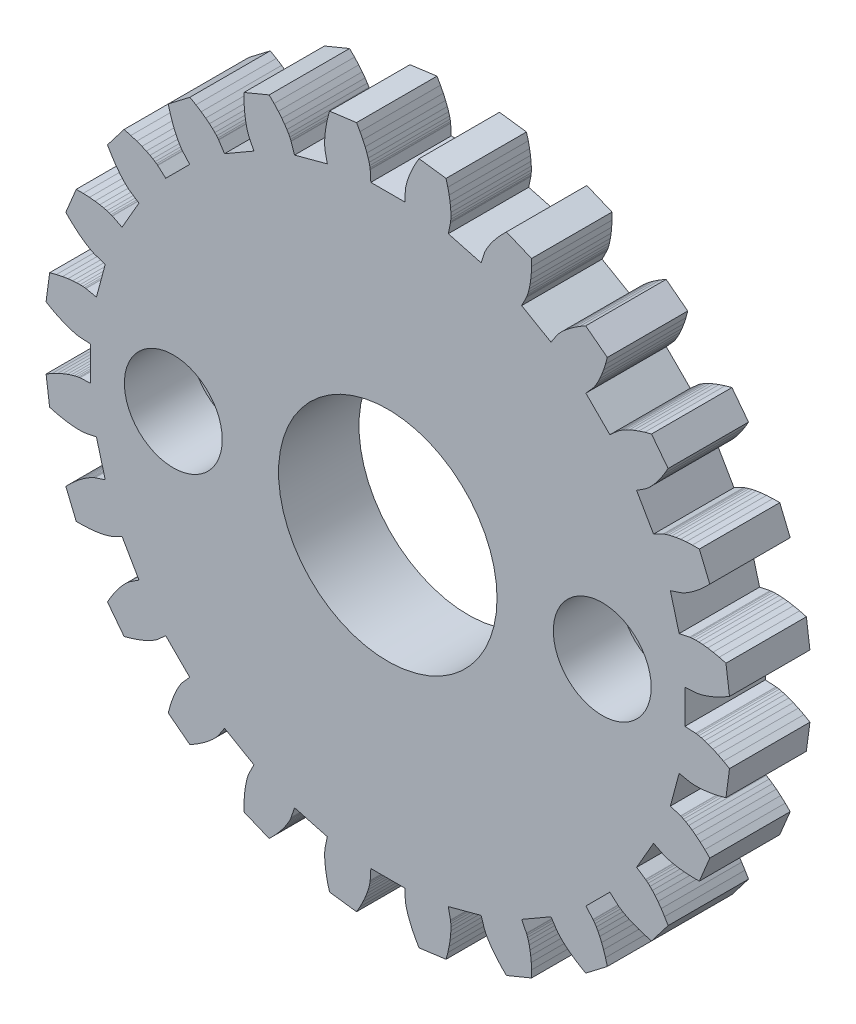
SolidWorks part; units mm, degrees
material "ABS"
ref_plane "Front Plane" through (0, 0, 0) normal (0, 0, 1) x (1, 0, 0)
ref_plane "Top Plane" through (0, 0, 0) normal (0, 1, 0) x (1, 0, 0)
ref_plane "Right Plane" through (0, 0, 0) normal (1, 0, 0) x (0, 0, -1)
sketch "Model" plane through (0, 0, 0) normal (0, 0, 1) x (1, 0, 0)
  line L0 (11.4813, -0.6559) -> (11.0819, -0.6331)
  line L1 (11.0819, -0.6331) -> (11.0819, 0.6331)
  line L2 (11.4813, 0.6559) -> (11.0819, 0.6331)
  line L3 (11.4813, 0.6559) -> (11.495, 0.6571)
  line L4 (11.495, 0.6571) -> (11.5358, 0.6626)
  line L5 (11.5358, 0.6626) -> (11.6033, 0.6749)
  line L6 (11.6033, 0.6749) -> (11.697, 0.6968)
  line L7 (11.697, 0.6968) -> (11.8158, 0.7307)
  line L8 (11.8158, 0.7307) -> (11.9589, 0.7792)
  line L9 (11.9589, 0.7792) -> (12.125, 0.8446)
  line L10 (12.125, 0.8446) -> (12.3128, 0.9294)
  line L11 (12.3128, 0.9294) -> (12.5206, 1.0358)
  line L12 (12.5206, 1.0358) -> (12.7468, 1.1658)
  line L13 (11.2598, 2.338) -> (11.2734, 2.3404)
  line L14 (11.2734, 2.3404) -> (11.3142, 2.3457)
  line L15 (11.3142, 2.3457) -> (11.3827, 2.3512)
  line L16 (11.3827, 2.3512) -> (11.4787, 2.3543)
  line L17 (11.4787, 2.3543) -> (11.6023, 2.3524)
  line L18 (11.6023, 2.3524) -> (11.7531, 2.3426)
  line L19 (11.7531, 2.3426) -> (11.9305, 2.3223)
  line L20 (11.9305, 2.3223) -> (12.1338, 2.289)
  line L21 (12.1338, 2.289) -> (12.362, 2.2401)
  line L22 (12.362, 2.2401) -> (12.6142, 2.173)
  line L23 (12.7468, 1.1658) -> (12.6142, 2.173)
  line L24 (11.2598, 2.338) -> (10.8682, 2.2567)
  line L25 (10.8682, 2.2567) -> (10.5405, 3.4797)
  line L26 (10.9203, 3.6051) -> (10.5405, 3.4797)
  line L27 (10.9203, 3.6051) -> (10.9332, 3.6098)
  line L28 (10.9332, 3.6098) -> (10.9712, 3.6257)
  line L29 (10.9712, 3.6257) -> (11.0333, 3.6551)
  line L30 (11.0333, 3.6551) -> (11.1181, 3.7004)
  line L31 (11.1181, 3.7004) -> (11.2241, 3.764)
  line L32 (11.2241, 3.764) -> (11.3497, 3.8478)
  line L33 (11.3497, 3.8478) -> (11.4933, 3.954)
  line L34 (11.4933, 3.954) -> (11.6527, 4.0845)
  line L35 (11.6527, 4.0845) -> (11.8259, 4.241)
  line L36 (11.8259, 4.241) -> (12.0107, 4.4252)
  line L37 (10.271, 5.1726) -> (10.2835, 5.1784)
  line L38 (10.2835, 5.1784) -> (10.3216, 5.1941)
  line L39 (10.3216, 5.1941) -> (10.3863, 5.2172)
  line L40 (10.3863, 5.2172) -> (10.4783, 5.245)
  line L41 (10.4783, 5.245) -> (10.5981, 5.2751)
  line L42 (10.5981, 5.2751) -> (10.7463, 5.3047)
  line L43 (10.7463, 5.3047) -> (10.9229, 5.331)
  line L44 (10.9229, 5.331) -> (11.1279, 5.3515)
  line L45 (11.1279, 5.3515) -> (11.361, 5.3633)
  line L46 (11.361, 5.3633) -> (11.622, 5.3638)
  line L47 (12.0107, 4.4252) -> (11.622, 5.3638)
  line L48 (10.271, 5.1726) -> (9.9138, 4.9927)
  line L49 (9.9138, 4.9927) -> (9.2807, 6.0892)
  line L50 (9.6151, 6.3087) -> (9.2807, 6.0892)
  line L51 (9.6151, 6.3087) -> (9.6264, 6.3166)
  line L52 (9.6264, 6.3166) -> (9.659, 6.3417)
  line L53 (9.659, 6.3417) -> (9.7113, 6.3862)
  line L54 (9.7113, 6.3862) -> (9.7815, 6.4519)
  line L55 (9.7815, 6.4519) -> (9.8675, 6.5407)
  line L56 (9.8675, 6.5407) -> (9.9671, 6.6542)
  line L57 (9.9671, 6.6542) -> (10.0783, 6.794)
  line L58 (10.0783, 6.794) -> (10.1985, 6.9613)
  line L59 (10.1985, 6.9613) -> (10.3253, 7.1573)
  line L60 (10.3253, 7.1573) -> (10.4561, 7.383)
  line L61 (8.5823, 7.6547) -> (8.5928, 7.6635)
  line L62 (8.5928, 7.6635) -> (8.6256, 7.6885)
  line L63 (8.6256, 7.6885) -> (8.6821, 7.7275)
  line L64 (8.6821, 7.7275) -> (8.7637, 7.7783)
  line L65 (8.7637, 7.7783) -> (8.8717, 7.8384)
  line L66 (8.8717, 7.8384) -> (9.0072, 7.9053)
  line L67 (9.0072, 7.9053) -> (9.1709, 7.9764)
  line L68 (9.1709, 7.9764) -> (9.3636, 8.0492)
  line L69 (9.3636, 8.0492) -> (9.5858, 8.121)
  line L70 (9.5858, 8.121) -> (9.8377, 8.189)
  line L71 (10.4561, 7.383) -> (9.8377, 8.189)
  line L72 (8.5823, 7.6547) -> (8.2838, 7.3885)
  line L73 (8.2838, 7.3885) -> (7.3885, 8.2838)
  line L74 (7.6547, 8.5823) -> (7.3885, 8.2838)
  line L75 (7.6547, 8.5823) -> (7.6635, 8.5928)
  line L76 (7.6635, 8.5928) -> (7.6885, 8.6256)
  line L77 (7.6885, 8.6256) -> (7.7275, 8.6821)
  line L78 (7.7275, 8.6821) -> (7.7783, 8.7637)
  line L79 (7.7783, 8.7637) -> (7.8384, 8.8717)
  line L80 (7.8384, 8.8717) -> (7.9053, 9.0072)
  line L81 (7.9053, 9.0072) -> (7.9764, 9.1709)
  line L82 (7.9764, 9.1709) -> (8.0492, 9.3636)
  line L83 (8.0492, 9.3636) -> (8.121, 9.5858)
  line L84 (8.121, 9.5858) -> (8.189, 9.8377)
  line L85 (6.3087, 9.6151) -> (6.3166, 9.6264)
  line L86 (6.3166, 9.6264) -> (6.3417, 9.659)
  line L87 (6.3417, 9.659) -> (6.3862, 9.7113)
  line L88 (6.3862, 9.7113) -> (6.4519, 9.7815)
  line L89 (6.4519, 9.7815) -> (6.5407, 9.8675)
  line L90 (6.5407, 9.8675) -> (6.6542, 9.9671)
  line L91 (6.6542, 9.9671) -> (6.794, 10.0783)
  line L92 (6.794, 10.0783) -> (6.9613, 10.1985)
  line L93 (6.9613, 10.1985) -> (7.1573, 10.3253)
  line L94 (7.1573, 10.3253) -> (7.383, 10.4561)
  line L95 (8.189, 9.8377) -> (7.383, 10.4561)
  line L96 (6.3087, 9.6151) -> (6.0892, 9.2807)
  line L97 (6.0892, 9.2807) -> (4.9927, 9.9138)
  line L98 (5.1726, 10.271) -> (4.9927, 9.9138)
  line L99 (5.1726, 10.271) -> (5.1784, 10.2835)
  line L100 (5.1784, 10.2835) -> (5.1941, 10.3216)
  line L101 (5.1941, 10.3216) -> (5.2172, 10.3863)
  line L102 (5.2172, 10.3863) -> (5.245, 10.4783)
  line L103 (5.245, 10.4783) -> (5.2751, 10.5981)
  line L104 (5.2751, 10.5981) -> (5.3047, 10.7463)
  line L105 (5.3047, 10.7463) -> (5.331, 10.9229)
  line L106 (5.331, 10.9229) -> (5.3515, 11.1279)
  line L107 (5.3515, 11.1279) -> (5.3633, 11.361)
  line L108 (5.3633, 11.361) -> (5.3638, 11.622)
  line L109 (3.6051, 10.9203) -> (3.6098, 10.9332)
  line L110 (3.6098, 10.9332) -> (3.6257, 10.9712)
  line L111 (3.6257, 10.9712) -> (3.6551, 11.0333)
  line L112 (3.6551, 11.0333) -> (3.7004, 11.1181)
  line L113 (3.7004, 11.1181) -> (3.764, 11.2241)
  line L114 (3.764, 11.2241) -> (3.8478, 11.3497)
  line L115 (3.8478, 11.3497) -> (3.954, 11.4933)
  line L116 (3.954, 11.4933) -> (4.0845, 11.6527)
  line L117 (4.0845, 11.6527) -> (4.241, 11.8259)
  line L118 (4.241, 11.8259) -> (4.4252, 12.0107)
  line L119 (5.3638, 11.622) -> (4.4252, 12.0107)
  line L120 (3.6051, 10.9203) -> (3.4797, 10.5405)
  line L121 (3.4797, 10.5405) -> (2.2567, 10.8682)
  line L122 (2.338, 11.2598) -> (2.2567, 10.8682)
  line L123 (2.338, 11.2598) -> (2.3404, 11.2734)
  line L124 (2.3404, 11.2734) -> (2.3457, 11.3142)
  line L125 (2.3457, 11.3142) -> (2.3512, 11.3827)
  line L126 (2.3512, 11.3827) -> (2.3543, 11.4787)
  line L127 (2.3543, 11.4787) -> (2.3524, 11.6023)
  line L128 (2.3524, 11.6023) -> (2.3426, 11.7531)
  line L129 (2.3426, 11.7531) -> (2.3223, 11.9305)
  line L130 (2.3223, 11.9305) -> (2.289, 12.1338)
  line L131 (2.289, 12.1338) -> (2.2401, 12.362)
  line L132 (2.2401, 12.362) -> (2.173, 12.6142)
  line L133 (0.6559, 11.4813) -> (0.6571, 11.495)
  line L134 (0.6571, 11.495) -> (0.6626, 11.5358)
  line L135 (0.6626, 11.5358) -> (0.6749, 11.6033)
  line L136 (0.6749, 11.6033) -> (0.6968, 11.697)
  line L137 (0.6968, 11.697) -> (0.7307, 11.8158)
  line L138 (0.7307, 11.8158) -> (0.7792, 11.9589)
  line L139 (0.7792, 11.9589) -> (0.8446, 12.125)
  line L140 (0.8446, 12.125) -> (0.9294, 12.3128)
  line L141 (0.9294, 12.3128) -> (1.0358, 12.5206)
  line L142 (1.0358, 12.5206) -> (1.1658, 12.7468)
  line L143 (2.173, 12.6142) -> (1.1658, 12.7468)
  line L144 (0.6559, 11.4813) -> (0.6331, 11.0819)
  line L145 (0.6331, 11.0819) -> (-0.6331, 11.0819)
  line L146 (-0.6559, 11.4813) -> (-0.6331, 11.0819)
  line L147 (-0.6559, 11.4813) -> (-0.6571, 11.495)
  line L148 (-0.6571, 11.495) -> (-0.6626, 11.5358)
  line L149 (-0.6626, 11.5358) -> (-0.6749, 11.6033)
  line L150 (-0.6749, 11.6033) -> (-0.6968, 11.697)
  line L151 (-0.6968, 11.697) -> (-0.7307, 11.8158)
  line L152 (-0.7307, 11.8158) -> (-0.7792, 11.9589)
  line L153 (-0.7792, 11.9589) -> (-0.8446, 12.125)
  line L154 (-0.8446, 12.125) -> (-0.9294, 12.3128)
  line L155 (-0.9294, 12.3128) -> (-1.0358, 12.5206)
  line L156 (-1.0358, 12.5206) -> (-1.1658, 12.7468)
  line L157 (-2.338, 11.2598) -> (-2.3404, 11.2734)
  line L158 (-2.3404, 11.2734) -> (-2.3457, 11.3142)
  line L159 (-2.3457, 11.3142) -> (-2.3512, 11.3827)
  line L160 (-2.3512, 11.3827) -> (-2.3543, 11.4787)
  line L161 (-2.3543, 11.4787) -> (-2.3524, 11.6023)
  line L162 (-2.3524, 11.6023) -> (-2.3426, 11.7531)
  line L163 (-2.3426, 11.7531) -> (-2.3223, 11.9305)
  line L164 (-2.3223, 11.9305) -> (-2.289, 12.1338)
  line L165 (-2.289, 12.1338) -> (-2.2401, 12.362)
  line L166 (-2.2401, 12.362) -> (-2.173, 12.6142)
  line L167 (-1.1658, 12.7468) -> (-2.173, 12.6142)
  line L168 (-2.338, 11.2598) -> (-2.2567, 10.8682)
  line L169 (-2.2567, 10.8682) -> (-3.4797, 10.5405)
  line L170 (-3.6051, 10.9203) -> (-3.4797, 10.5405)
  line L171 (-3.6051, 10.9203) -> (-3.6098, 10.9332)
  line L172 (-3.6098, 10.9332) -> (-3.6257, 10.9712)
  line L173 (-3.6257, 10.9712) -> (-3.6551, 11.0333)
  line L174 (-3.6551, 11.0333) -> (-3.7004, 11.1181)
  line L175 (-3.7004, 11.1181) -> (-3.764, 11.2241)
  line L176 (-3.764, 11.2241) -> (-3.8478, 11.3497)
  line L177 (-3.8478, 11.3497) -> (-3.954, 11.4933)
  line L178 (-3.954, 11.4933) -> (-4.0845, 11.6527)
  line L179 (-4.0845, 11.6527) -> (-4.241, 11.8259)
  line L180 (-4.241, 11.8259) -> (-4.4252, 12.0107)
  line L181 (-5.1726, 10.271) -> (-5.1784, 10.2835)
  line L182 (-5.1784, 10.2835) -> (-5.1941, 10.3216)
  line L183 (-5.1941, 10.3216) -> (-5.2172, 10.3863)
  line L184 (-5.2172, 10.3863) -> (-5.245, 10.4783)
  line L185 (-5.245, 10.4783) -> (-5.2751, 10.5981)
  line L186 (-5.2751, 10.5981) -> (-5.3047, 10.7463)
  line L187 (-5.3047, 10.7463) -> (-5.331, 10.9229)
  line L188 (-5.331, 10.9229) -> (-5.3515, 11.1279)
  line L189 (-5.3515, 11.1279) -> (-5.3633, 11.361)
  line L190 (-5.3633, 11.361) -> (-5.3638, 11.622)
  line L191 (-4.4252, 12.0107) -> (-5.3638, 11.622)
  line L192 (-5.1726, 10.271) -> (-4.9927, 9.9138)
  line L193 (-4.9927, 9.9138) -> (-6.0892, 9.2807)
  line L194 (-6.3087, 9.6151) -> (-6.0892, 9.2807)
  line L195 (-6.3087, 9.6151) -> (-6.3166, 9.6264)
  line L196 (-6.3166, 9.6264) -> (-6.3417, 9.659)
  line L197 (-6.3417, 9.659) -> (-6.3862, 9.7113)
  line L198 (-6.3862, 9.7113) -> (-6.4519, 9.7815)
  line L199 (-6.4519, 9.7815) -> (-6.5407, 9.8675)
  line L200 (-6.5407, 9.8675) -> (-6.6542, 9.9671)
  line L201 (-6.6542, 9.9671) -> (-6.794, 10.0783)
  line L202 (-6.794, 10.0783) -> (-6.9613, 10.1985)
  line L203 (-6.9613, 10.1985) -> (-7.1573, 10.3253)
  line L204 (-7.1573, 10.3253) -> (-7.383, 10.4561)
  line L205 (-7.6547, 8.5823) -> (-7.6635, 8.5928)
  line L206 (-7.6635, 8.5928) -> (-7.6885, 8.6256)
  line L207 (-7.6885, 8.6256) -> (-7.7275, 8.6821)
  line L208 (-7.7275, 8.6821) -> (-7.7783, 8.7637)
  line L209 (-7.7783, 8.7637) -> (-7.8384, 8.8717)
  line L210 (-7.8384, 8.8717) -> (-7.9053, 9.0072)
  line L211 (-7.9053, 9.0072) -> (-7.9764, 9.1709)
  line L212 (-7.9764, 9.1709) -> (-8.0492, 9.3636)
  line L213 (-8.0492, 9.3636) -> (-8.121, 9.5858)
  line L214 (-8.121, 9.5858) -> (-8.189, 9.8377)
  line L215 (-7.383, 10.4561) -> (-8.189, 9.8377)
  line L216 (-7.6547, 8.5823) -> (-7.3885, 8.2838)
  line L217 (-7.3885, 8.2838) -> (-8.2838, 7.3885)
  line L218 (-8.5823, 7.6547) -> (-8.2838, 7.3885)
  line L219 (-8.5823, 7.6547) -> (-8.5928, 7.6635)
  line L220 (-8.5928, 7.6635) -> (-8.6256, 7.6885)
  line L221 (-8.6256, 7.6885) -> (-8.6821, 7.7275)
  line L222 (-8.6821, 7.7275) -> (-8.7637, 7.7783)
  line L223 (-8.7637, 7.7783) -> (-8.8717, 7.8384)
  line L224 (-8.8717, 7.8384) -> (-9.0072, 7.9053)
  line L225 (-9.0072, 7.9053) -> (-9.1709, 7.9764)
  line L226 (-9.1709, 7.9764) -> (-9.3636, 8.0492)
  line L227 (-9.3636, 8.0492) -> (-9.5858, 8.121)
  line L228 (-9.5858, 8.121) -> (-9.8377, 8.189)
  line L229 (-9.6151, 6.3087) -> (-9.6264, 6.3166)
  line L230 (-9.6264, 6.3166) -> (-9.659, 6.3417)
  line L231 (-9.659, 6.3417) -> (-9.7113, 6.3862)
  line L232 (-9.7113, 6.3862) -> (-9.7815, 6.4519)
  line L233 (-9.7815, 6.4519) -> (-9.8675, 6.5407)
  line L234 (-9.8675, 6.5407) -> (-9.9671, 6.6542)
  line L235 (-9.9671, 6.6542) -> (-10.0783, 6.794)
  line L236 (-10.0783, 6.794) -> (-10.1985, 6.9613)
  line L237 (-10.1985, 6.9613) -> (-10.3253, 7.1573)
  line L238 (-10.3253, 7.1573) -> (-10.4561, 7.383)
  line L239 (-9.8377, 8.189) -> (-10.4561, 7.383)
  line L240 (-9.6151, 6.3087) -> (-9.2807, 6.0892)
  line L241 (-9.2807, 6.0892) -> (-9.9138, 4.9927)
  line L242 (-10.271, 5.1726) -> (-9.9138, 4.9927)
  line L243 (-10.271, 5.1726) -> (-10.2835, 5.1784)
  line L244 (-10.2835, 5.1784) -> (-10.3216, 5.1941)
  line L245 (-10.3216, 5.1941) -> (-10.3863, 5.2172)
  line L246 (-10.3863, 5.2172) -> (-10.4783, 5.245)
  line L247 (-10.4783, 5.245) -> (-10.5981, 5.2751)
  line L248 (-10.5981, 5.2751) -> (-10.7463, 5.3047)
  line L249 (-10.7463, 5.3047) -> (-10.9229, 5.331)
  line L250 (-10.9229, 5.331) -> (-11.1279, 5.3515)
  line L251 (-11.1279, 5.3515) -> (-11.361, 5.3633)
  line L252 (-11.361, 5.3633) -> (-11.622, 5.3638)
  line L253 (-10.9203, 3.6051) -> (-10.9332, 3.6098)
  line L254 (-10.9332, 3.6098) -> (-10.9712, 3.6257)
  line L255 (-10.9712, 3.6257) -> (-11.0333, 3.6551)
  line L256 (-11.0333, 3.6551) -> (-11.1181, 3.7004)
  line L257 (-11.1181, 3.7004) -> (-11.2241, 3.764)
  line L258 (-11.2241, 3.764) -> (-11.3497, 3.8478)
  line L259 (-11.3497, 3.8478) -> (-11.4933, 3.954)
  line L260 (-11.4933, 3.954) -> (-11.6527, 4.0845)
  line L261 (-11.6527, 4.0845) -> (-11.8259, 4.241)
  line L262 (-11.8259, 4.241) -> (-12.0107, 4.4252)
  line L263 (-11.622, 5.3638) -> (-12.0107, 4.4252)
  line L264 (-10.9203, 3.6051) -> (-10.5405, 3.4797)
  line L265 (-10.5405, 3.4797) -> (-10.8682, 2.2567)
  line L266 (-11.2598, 2.338) -> (-10.8682, 2.2567)
  line L267 (-11.2598, 2.338) -> (-11.2734, 2.3404)
  line L268 (-11.2734, 2.3404) -> (-11.3142, 2.3457)
  line L269 (-11.3142, 2.3457) -> (-11.3827, 2.3512)
  line L270 (-11.3827, 2.3512) -> (-11.4787, 2.3543)
  line L271 (-11.4787, 2.3543) -> (-11.6023, 2.3524)
  line L272 (-11.6023, 2.3524) -> (-11.7531, 2.3426)
  line L273 (-11.7531, 2.3426) -> (-11.9305, 2.3223)
  line L274 (-11.9305, 2.3223) -> (-12.1338, 2.289)
  line L275 (-12.1338, 2.289) -> (-12.362, 2.2401)
  line L276 (-12.362, 2.2401) -> (-12.6142, 2.173)
  line L277 (-11.4813, 0.6559) -> (-11.495, 0.6571)
  line L278 (-11.495, 0.6571) -> (-11.5358, 0.6626)
  line L279 (-11.5358, 0.6626) -> (-11.6033, 0.6749)
  line L280 (-11.6033, 0.6749) -> (-11.697, 0.6968)
  line L281 (-11.697, 0.6968) -> (-11.8158, 0.7307)
  line L282 (-11.8158, 0.7307) -> (-11.9589, 0.7792)
  line L283 (-11.9589, 0.7792) -> (-12.125, 0.8446)
  line L284 (-12.125, 0.8446) -> (-12.3128, 0.9294)
  line L285 (-12.3128, 0.9294) -> (-12.5206, 1.0358)
  line L286 (-12.5206, 1.0358) -> (-12.7468, 1.1658)
  line L287 (-12.6142, 2.173) -> (-12.7468, 1.1658)
  line L288 (-11.4813, 0.6559) -> (-11.0819, 0.6331)
  line L289 (-11.0819, 0.6331) -> (-11.0819, -0.6331)
  line L290 (-11.4813, -0.6559) -> (-11.0819, -0.6331)
  line L291 (-11.4813, -0.6559) -> (-11.495, -0.6571)
  line L292 (-11.495, -0.6571) -> (-11.5358, -0.6626)
  line L293 (-11.5358, -0.6626) -> (-11.6033, -0.6749)
  line L294 (-11.6033, -0.6749) -> (-11.697, -0.6968)
  line L295 (-11.697, -0.6968) -> (-11.8158, -0.7307)
  line L296 (-11.8158, -0.7307) -> (-11.9589, -0.7792)
  line L297 (-11.9589, -0.7792) -> (-12.125, -0.8446)
  line L298 (-12.125, -0.8446) -> (-12.3128, -0.9294)
  line L299 (-12.3128, -0.9294) -> (-12.5206, -1.0358)
  line L300 (-12.5206, -1.0358) -> (-12.7468, -1.1658)
  line L301 (-11.2598, -2.338) -> (-11.2734, -2.3404)
  line L302 (-11.2734, -2.3404) -> (-11.3142, -2.3457)
  line L303 (-11.3142, -2.3457) -> (-11.3827, -2.3512)
  line L304 (-11.3827, -2.3512) -> (-11.4787, -2.3543)
  line L305 (-11.4787, -2.3543) -> (-11.6023, -2.3524)
  line L306 (-11.6023, -2.3524) -> (-11.7531, -2.3426)
  line L307 (-11.7531, -2.3426) -> (-11.9305, -2.3223)
  line L308 (-11.9305, -2.3223) -> (-12.1338, -2.289)
  line L309 (-12.1338, -2.289) -> (-12.362, -2.2401)
  line L310 (-12.362, -2.2401) -> (-12.6142, -2.173)
  line L311 (-12.7468, -1.1658) -> (-12.6142, -2.173)
  line L312 (-11.2598, -2.338) -> (-10.8682, -2.2567)
  line L313 (-10.8682, -2.2567) -> (-10.5405, -3.4797)
  line L314 (-10.9203, -3.6051) -> (-10.5405, -3.4797)
  line L315 (-10.9203, -3.6051) -> (-10.9332, -3.6098)
  line L316 (-10.9332, -3.6098) -> (-10.9712, -3.6257)
  line L317 (-10.9712, -3.6257) -> (-11.0333, -3.6551)
  line L318 (-11.0333, -3.6551) -> (-11.1181, -3.7004)
  line L319 (-11.1181, -3.7004) -> (-11.2241, -3.764)
  line L320 (-11.2241, -3.764) -> (-11.3497, -3.8478)
  line L321 (-11.3497, -3.8478) -> (-11.4933, -3.954)
  line L322 (-11.4933, -3.954) -> (-11.6527, -4.0845)
  line L323 (-11.6527, -4.0845) -> (-11.8259, -4.241)
  line L324 (-11.8259, -4.241) -> (-12.0107, -4.4252)
  line L325 (-10.271, -5.1726) -> (-10.2835, -5.1784)
  line L326 (-10.2835, -5.1784) -> (-10.3216, -5.1941)
  line L327 (-10.3216, -5.1941) -> (-10.3863, -5.2172)
  line L328 (-10.3863, -5.2172) -> (-10.4783, -5.245)
  line L329 (-10.4783, -5.245) -> (-10.5981, -5.2751)
  line L330 (-10.5981, -5.2751) -> (-10.7463, -5.3047)
  line L331 (-10.7463, -5.3047) -> (-10.9229, -5.331)
  line L332 (-10.9229, -5.331) -> (-11.1279, -5.3515)
  line L333 (-11.1279, -5.3515) -> (-11.361, -5.3633)
  line L334 (-11.361, -5.3633) -> (-11.622, -5.3638)
  line L335 (-12.0107, -4.4252) -> (-11.622, -5.3638)
  line L336 (-10.271, -5.1726) -> (-9.9138, -4.9927)
  line L337 (-9.9138, -4.9927) -> (-9.2807, -6.0892)
  line L338 (-9.6151, -6.3087) -> (-9.2807, -6.0892)
  line L339 (-9.6151, -6.3087) -> (-9.6264, -6.3166)
  line L340 (-9.6264, -6.3166) -> (-9.659, -6.3417)
  line L341 (-9.659, -6.3417) -> (-9.7113, -6.3862)
  line L342 (-9.7113, -6.3862) -> (-9.7815, -6.4519)
  line L343 (-9.7815, -6.4519) -> (-9.8675, -6.5407)
  line L344 (-9.8675, -6.5407) -> (-9.9671, -6.6542)
  line L345 (-9.9671, -6.6542) -> (-10.0783, -6.794)
  line L346 (-10.0783, -6.794) -> (-10.1985, -6.9613)
  line L347 (-10.1985, -6.9613) -> (-10.3253, -7.1573)
  line L348 (-10.3253, -7.1573) -> (-10.4561, -7.383)
  line L349 (-8.5823, -7.6547) -> (-8.5928, -7.6635)
  line L350 (-8.5928, -7.6635) -> (-8.6256, -7.6885)
  line L351 (-8.6256, -7.6885) -> (-8.6821, -7.7275)
  line L352 (-8.6821, -7.7275) -> (-8.7637, -7.7783)
  line L353 (-8.7637, -7.7783) -> (-8.8717, -7.8384)
  line L354 (-8.8717, -7.8384) -> (-9.0072, -7.9053)
  line L355 (-9.0072, -7.9053) -> (-9.1709, -7.9764)
  line L356 (-9.1709, -7.9764) -> (-9.3636, -8.0492)
  line L357 (-9.3636, -8.0492) -> (-9.5858, -8.121)
  line L358 (-9.5858, -8.121) -> (-9.8377, -8.189)
  line L359 (-10.4561, -7.383) -> (-9.8377, -8.189)
  line L360 (-8.5823, -7.6547) -> (-8.2838, -7.3885)
  line L361 (-8.2838, -7.3885) -> (-7.3885, -8.2838)
  line L362 (-7.6547, -8.5823) -> (-7.3885, -8.2838)
  line L363 (-7.6547, -8.5823) -> (-7.6635, -8.5928)
  line L364 (-7.6635, -8.5928) -> (-7.6885, -8.6256)
  line L365 (-7.6885, -8.6256) -> (-7.7275, -8.6821)
  line L366 (-7.7275, -8.6821) -> (-7.7783, -8.7637)
  line L367 (-7.7783, -8.7637) -> (-7.8384, -8.8717)
  line L368 (-7.8384, -8.8717) -> (-7.9053, -9.0072)
  line L369 (-7.9053, -9.0072) -> (-7.9764, -9.1709)
  line L370 (-7.9764, -9.1709) -> (-8.0492, -9.3636)
  line L371 (-8.0492, -9.3636) -> (-8.121, -9.5858)
  line L372 (-8.121, -9.5858) -> (-8.189, -9.8377)
  line L373 (-6.3087, -9.6151) -> (-6.3166, -9.6264)
  line L374 (-6.3166, -9.6264) -> (-6.3417, -9.659)
  line L375 (-6.3417, -9.659) -> (-6.3862, -9.7113)
  line L376 (-6.3862, -9.7113) -> (-6.4519, -9.7815)
  line L377 (-6.4519, -9.7815) -> (-6.5407, -9.8675)
  line L378 (-6.5407, -9.8675) -> (-6.6542, -9.9671)
  line L379 (-6.6542, -9.9671) -> (-6.794, -10.0783)
  line L380 (-6.794, -10.0783) -> (-6.9613, -10.1985)
  line L381 (-6.9613, -10.1985) -> (-7.1573, -10.3253)
  line L382 (-7.1573, -10.3253) -> (-7.383, -10.4561)
  line L383 (-8.189, -9.8377) -> (-7.383, -10.4561)
  line L384 (-6.3087, -9.6151) -> (-6.0892, -9.2807)
  line L385 (-6.0892, -9.2807) -> (-4.9927, -9.9138)
  line L386 (-5.1726, -10.271) -> (-4.9927, -9.9138)
  line L387 (-5.1726, -10.271) -> (-5.1784, -10.2835)
  line L388 (-5.1784, -10.2835) -> (-5.1941, -10.3216)
  line L389 (-5.1941, -10.3216) -> (-5.2172, -10.3863)
  line L390 (-5.2172, -10.3863) -> (-5.245, -10.4783)
  line L391 (-5.245, -10.4783) -> (-5.2751, -10.5981)
  line L392 (-5.2751, -10.5981) -> (-5.3047, -10.7463)
  line L393 (-5.3047, -10.7463) -> (-5.331, -10.9229)
  line L394 (-5.331, -10.9229) -> (-5.3515, -11.1279)
  line L395 (-5.3515, -11.1279) -> (-5.3633, -11.361)
  line L396 (-5.3633, -11.361) -> (-5.3638, -11.622)
  line L397 (-3.6051, -10.9203) -> (-3.6098, -10.9332)
  line L398 (-3.6098, -10.9332) -> (-3.6257, -10.9712)
  line L399 (-3.6257, -10.9712) -> (-3.6551, -11.0333)
  line L400 (-3.6551, -11.0333) -> (-3.7004, -11.1181)
  line L401 (-3.7004, -11.1181) -> (-3.764, -11.2241)
  line L402 (-3.764, -11.2241) -> (-3.8478, -11.3497)
  line L403 (-3.8478, -11.3497) -> (-3.954, -11.4933)
  line L404 (-3.954, -11.4933) -> (-4.0845, -11.6527)
  line L405 (-4.0845, -11.6527) -> (-4.241, -11.8259)
  line L406 (-4.241, -11.8259) -> (-4.4252, -12.0107)
  line L407 (-5.3638, -11.622) -> (-4.4252, -12.0107)
  line L408 (-3.6051, -10.9203) -> (-3.4797, -10.5405)
  line L409 (-3.4797, -10.5405) -> (-2.2567, -10.8682)
  line L410 (-2.338, -11.2598) -> (-2.2567, -10.8682)
  line L411 (-2.338, -11.2598) -> (-2.3404, -11.2734)
  line L412 (-2.3404, -11.2734) -> (-2.3457, -11.3142)
  line L413 (-2.3457, -11.3142) -> (-2.3512, -11.3827)
  line L414 (-2.3512, -11.3827) -> (-2.3543, -11.4787)
  line L415 (-2.3543, -11.4787) -> (-2.3524, -11.6023)
  line L416 (-2.3524, -11.6023) -> (-2.3426, -11.7531)
  line L417 (-2.3426, -11.7531) -> (-2.3223, -11.9305)
  line L418 (-2.3223, -11.9305) -> (-2.289, -12.1338)
  line L419 (-2.289, -12.1338) -> (-2.2401, -12.362)
  line L420 (-2.2401, -12.362) -> (-2.173, -12.6142)
  line L421 (-0.6559, -11.4813) -> (-0.6571, -11.495)
  line L422 (-0.6571, -11.495) -> (-0.6626, -11.5358)
  line L423 (-0.6626, -11.5358) -> (-0.6749, -11.6033)
  line L424 (-0.6749, -11.6033) -> (-0.6968, -11.697)
  line L425 (-0.6968, -11.697) -> (-0.7307, -11.8158)
  line L426 (-0.7307, -11.8158) -> (-0.7792, -11.9589)
  line L427 (-0.7792, -11.9589) -> (-0.8446, -12.125)
  line L428 (-0.8446, -12.125) -> (-0.9294, -12.3128)
  line L429 (-0.9294, -12.3128) -> (-1.0358, -12.5206)
  line L430 (-1.0358, -12.5206) -> (-1.1658, -12.7468)
  line L431 (-2.173, -12.6142) -> (-1.1658, -12.7468)
  line L432 (-0.6559, -11.4813) -> (-0.6331, -11.0819)
  line L433 (-0.6331, -11.0819) -> (0.6331, -11.0819)
  line L434 (0.6559, -11.4813) -> (0.6331, -11.0819)
  line L435 (0.6559, -11.4813) -> (0.6571, -11.495)
  line L436 (0.6571, -11.495) -> (0.6626, -11.5358)
  line L437 (0.6626, -11.5358) -> (0.6749, -11.6033)
  line L438 (0.6749, -11.6033) -> (0.6968, -11.697)
  line L439 (0.6968, -11.697) -> (0.7307, -11.8158)
  line L440 (0.7307, -11.8158) -> (0.7792, -11.9589)
  line L441 (0.7792, -11.9589) -> (0.8446, -12.125)
  line L442 (0.8446, -12.125) -> (0.9294, -12.3128)
  line L443 (0.9294, -12.3128) -> (1.0358, -12.5206)
  line L444 (1.0358, -12.5206) -> (1.1658, -12.7468)
  line L445 (2.338, -11.2598) -> (2.3404, -11.2734)
  line L446 (2.3404, -11.2734) -> (2.3457, -11.3142)
  line L447 (2.3457, -11.3142) -> (2.3512, -11.3827)
  line L448 (2.3512, -11.3827) -> (2.3543, -11.4787)
  line L449 (2.3543, -11.4787) -> (2.3524, -11.6023)
  line L450 (2.3524, -11.6023) -> (2.3426, -11.7531)
  line L451 (2.3426, -11.7531) -> (2.3223, -11.9305)
  line L452 (2.3223, -11.9305) -> (2.289, -12.1338)
  line L453 (2.289, -12.1338) -> (2.2401, -12.362)
  line L454 (2.2401, -12.362) -> (2.173, -12.6142)
  line L455 (1.1658, -12.7468) -> (2.173, -12.6142)
  line L456 (2.338, -11.2598) -> (2.2567, -10.8682)
  line L457 (2.2567, -10.8682) -> (3.4797, -10.5405)
  line L458 (3.6051, -10.9203) -> (3.4797, -10.5405)
  line L459 (3.6051, -10.9203) -> (3.6098, -10.9332)
  line L460 (3.6098, -10.9332) -> (3.6257, -10.9712)
  line L461 (3.6257, -10.9712) -> (3.6551, -11.0333)
  line L462 (3.6551, -11.0333) -> (3.7004, -11.1181)
  line L463 (3.7004, -11.1181) -> (3.764, -11.2241)
  line L464 (3.764, -11.2241) -> (3.8478, -11.3497)
  line L465 (3.8478, -11.3497) -> (3.954, -11.4933)
  line L466 (3.954, -11.4933) -> (4.0845, -11.6527)
  line L467 (4.0845, -11.6527) -> (4.241, -11.8259)
  line L468 (4.241, -11.8259) -> (4.4252, -12.0107)
  line L469 (5.1726, -10.271) -> (5.1784, -10.2835)
  line L470 (5.1784, -10.2835) -> (5.1941, -10.3216)
  line L471 (5.1941, -10.3216) -> (5.2172, -10.3863)
  line L472 (5.2172, -10.3863) -> (5.245, -10.4783)
  line L473 (5.245, -10.4783) -> (5.2751, -10.5981)
  line L474 (5.2751, -10.5981) -> (5.3047, -10.7463)
  line L475 (5.3047, -10.7463) -> (5.331, -10.9229)
  line L476 (5.331, -10.9229) -> (5.3515, -11.1279)
  line L477 (5.3515, -11.1279) -> (5.3633, -11.361)
  line L478 (5.3633, -11.361) -> (5.3638, -11.622)
  line L479 (4.4252, -12.0107) -> (5.3638, -11.622)
  line L480 (5.1726, -10.271) -> (4.9927, -9.9138)
  line L481 (4.9927, -9.9138) -> (6.0892, -9.2807)
  line L482 (6.3087, -9.6151) -> (6.0892, -9.2807)
  line L483 (6.3087, -9.6151) -> (6.3166, -9.6264)
  line L484 (6.3166, -9.6264) -> (6.3417, -9.659)
  line L485 (6.3417, -9.659) -> (6.3862, -9.7113)
  line L486 (6.3862, -9.7113) -> (6.4519, -9.7815)
  line L487 (6.4519, -9.7815) -> (6.5407, -9.8675)
  line L488 (6.5407, -9.8675) -> (6.6542, -9.9671)
  line L489 (6.6542, -9.9671) -> (6.794, -10.0783)
  line L490 (6.794, -10.0783) -> (6.9613, -10.1985)
  line L491 (6.9613, -10.1985) -> (7.1573, -10.3253)
  line L492 (7.1573, -10.3253) -> (7.383, -10.4561)
  line L493 (7.6547, -8.5823) -> (7.6635, -8.5928)
  line L494 (7.6635, -8.5928) -> (7.6885, -8.6256)
  line L495 (7.6885, -8.6256) -> (7.7275, -8.6821)
  line L496 (7.7275, -8.6821) -> (7.7783, -8.7637)
  line L497 (7.7783, -8.7637) -> (7.8384, -8.8717)
  line L498 (7.8384, -8.8717) -> (7.9053, -9.0072)
  line L499 (7.9053, -9.0072) -> (7.9764, -9.1709)
  line L500 (7.9764, -9.1709) -> (8.0492, -9.3636)
  line L501 (8.0492, -9.3636) -> (8.121, -9.5858)
  line L502 (8.121, -9.5858) -> (8.189, -9.8377)
  line L503 (7.383, -10.4561) -> (8.189, -9.8377)
  line L504 (7.6547, -8.5823) -> (7.3885, -8.2838)
  line L505 (7.3885, -8.2838) -> (8.2838, -7.3885)
  line L506 (8.5823, -7.6547) -> (8.2838, -7.3885)
  line L507 (8.5823, -7.6547) -> (8.5928, -7.6635)
  line L508 (8.5928, -7.6635) -> (8.6256, -7.6885)
  line L509 (8.6256, -7.6885) -> (8.6821, -7.7275)
  line L510 (8.6821, -7.7275) -> (8.7637, -7.7783)
  line L511 (8.7637, -7.7783) -> (8.8717, -7.8384)
  line L512 (8.8717, -7.8384) -> (9.0072, -7.9053)
  line L513 (9.0072, -7.9053) -> (9.1709, -7.9764)
  line L514 (9.1709, -7.9764) -> (9.3636, -8.0492)
  line L515 (9.3636, -8.0492) -> (9.5858, -8.121)
  line L516 (9.5858, -8.121) -> (9.8377, -8.189)
  line L517 (9.6151, -6.3087) -> (9.6264, -6.3166)
  line L518 (9.6264, -6.3166) -> (9.659, -6.3417)
  line L519 (9.659, -6.3417) -> (9.7113, -6.3862)
  line L520 (9.7113, -6.3862) -> (9.7815, -6.4519)
  line L521 (9.7815, -6.4519) -> (9.8675, -6.5407)
  line L522 (9.8675, -6.5407) -> (9.9671, -6.6542)
  line L523 (9.9671, -6.6542) -> (10.0783, -6.794)
  line L524 (10.0783, -6.794) -> (10.1985, -6.9613)
  line L525 (10.1985, -6.9613) -> (10.3253, -7.1573)
  line L526 (10.3253, -7.1573) -> (10.4561, -7.383)
  line L527 (9.8377, -8.189) -> (10.4561, -7.383)
  line L528 (9.6151, -6.3087) -> (9.2807, -6.0892)
  line L529 (9.2807, -6.0892) -> (9.9138, -4.9927)
  line L530 (10.271, -5.1726) -> (9.9138, -4.9927)
  line L531 (10.271, -5.1726) -> (10.2835, -5.1784)
  line L532 (10.2835, -5.1784) -> (10.3216, -5.1941)
  line L533 (10.3216, -5.1941) -> (10.3863, -5.2172)
  line L534 (10.3863, -5.2172) -> (10.4783, -5.245)
  line L535 (10.4783, -5.245) -> (10.5981, -5.2751)
  line L536 (10.5981, -5.2751) -> (10.7463, -5.3047)
  line L537 (10.7463, -5.3047) -> (10.9229, -5.331)
  line L538 (10.9229, -5.331) -> (11.1279, -5.3515)
  line L539 (11.1279, -5.3515) -> (11.361, -5.3633)
  line L540 (11.361, -5.3633) -> (11.622, -5.3638)
  line L541 (10.9203, -3.6051) -> (10.9332, -3.6098)
  line L542 (10.9332, -3.6098) -> (10.9712, -3.6257)
  line L543 (10.9712, -3.6257) -> (11.0333, -3.6551)
  line L544 (11.0333, -3.6551) -> (11.1181, -3.7004)
  line L545 (11.1181, -3.7004) -> (11.2241, -3.764)
  line L546 (11.2241, -3.764) -> (11.3497, -3.8478)
  line L547 (11.3497, -3.8478) -> (11.4933, -3.954)
  line L548 (11.4933, -3.954) -> (11.6527, -4.0845)
  line L549 (11.6527, -4.0845) -> (11.8259, -4.241)
  line L550 (11.8259, -4.241) -> (12.0107, -4.4252)
  line L551 (11.622, -5.3638) -> (12.0107, -4.4252)
  line L552 (10.9203, -3.6051) -> (10.5405, -3.4797)
  line L553 (10.5405, -3.4797) -> (10.8682, -2.2567)
  line L554 (11.2598, -2.338) -> (10.8682, -2.2567)
  line L555 (11.2598, -2.338) -> (11.2734, -2.3404)
  line L556 (11.2734, -2.3404) -> (11.3142, -2.3457)
  line L557 (11.3142, -2.3457) -> (11.3827, -2.3512)
  line L558 (11.3827, -2.3512) -> (11.4787, -2.3543)
  line L559 (11.4787, -2.3543) -> (11.6023, -2.3524)
  line L560 (11.6023, -2.3524) -> (11.7531, -2.3426)
  line L561 (11.7531, -2.3426) -> (11.9305, -2.3223)
  line L562 (11.9305, -2.3223) -> (12.1338, -2.289)
  line L563 (12.1338, -2.289) -> (12.362, -2.2401)
  line L564 (12.362, -2.2401) -> (12.6142, -2.173)
  line L565 (11.4813, -0.6559) -> (11.495, -0.6571)
  line L566 (11.495, -0.6571) -> (11.5358, -0.6626)
  line L567 (11.5358, -0.6626) -> (11.6033, -0.6749)
  line L568 (11.6033, -0.6749) -> (11.697, -0.6968)
  line L569 (11.697, -0.6968) -> (11.8158, -0.7307)
  line L570 (11.8158, -0.7307) -> (11.9589, -0.7792)
  line L571 (11.9589, -0.7792) -> (12.125, -0.8446)
  line L572 (12.125, -0.8446) -> (12.3128, -0.9294)
  line L573 (12.3128, -0.9294) -> (12.5206, -1.0358)
  line L574 (12.5206, -1.0358) -> (12.7468, -1.1658)
  line L575 (12.6142, -2.173) -> (12.7468, -1.1658)
extrude "Main Gear Body" add sketch "Model" along normal blind 3
sketch "Sketch1" plane through (0, 0, 3) normal (0, 0, 1) x (1, 0, 0)
  line L0 (-8, 0) -> (8, 0) construction
  circle A0 centre (0, 0) radius 4.075
  circle A1 centre (-8, 0) radius 1.15
  circle A2 centre (8, 0) radius 1.15
  dimension "D1" = 16
  dimension "D2" = 2.3
  dimension "D3" = 8.15
extrude "Servo Clearance" cut sketch "Sketch1" against normal through all
sketch "Sketch2" plane through (0, 0, 3) normal (0, 0, 1) x (1, 0, 0)
  circle A0 centre (8, 0) radius 1.825
  circle A1 centre (-8, 0) radius 1.825
  circle A3 centre (-8, 0) radius 1.15 construction
  circle A4 centre (8, 0) radius 1.15 construction
  dimension "D1" = 3.65
extrude "Bolt Head Clearance" cut sketch "Sketch2" against normal blind 2.5
ref_point "Point1"
equation "\"D3@Sketch1\"=8+\"print fit@values@params_print.SLDPRT\""
equation "\"D1@Sketch2\"=3.5+\"print fit@values@params_print.SLDPRT\""
